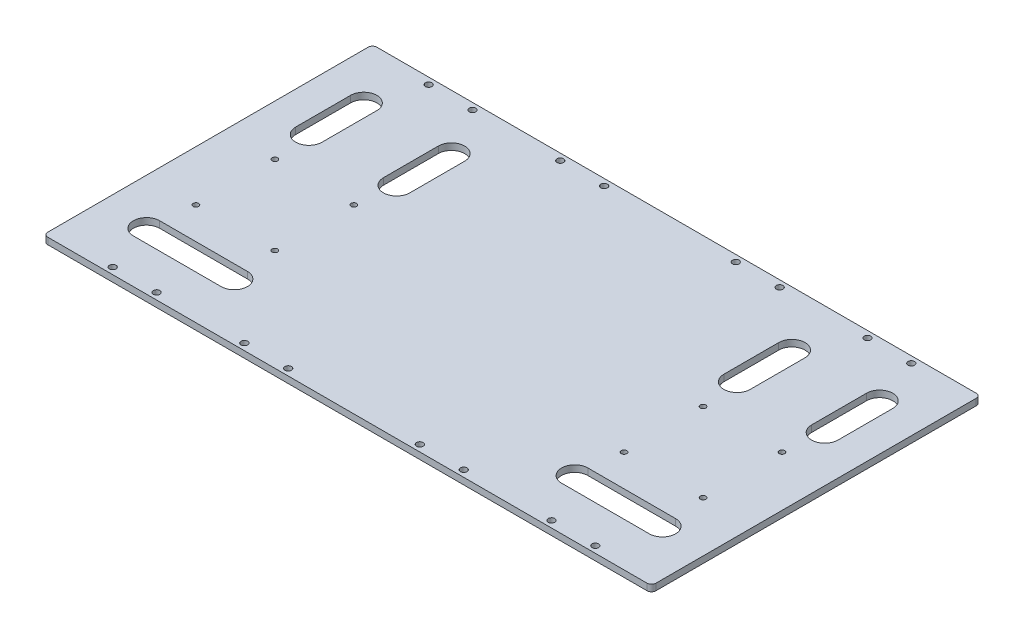
SolidWorks part; units mm, degrees
ref_plane "前视基准面" through (0, 0, 0) normal (0, 0, 1) x (1, 0, 0)
ref_plane "上视基准面" through (0, 0, 0) normal (0, 1, 0) x (1, 0, 0)
ref_plane "右视基准面" through (0, 0, 0) normal (1, 0, 0) x (0, 0, -1)
other "Configuration Table"
sketch "草图1" plane through (0, 0, 0) normal (0, 1, 0) x (1, 0, 0)
  line L9 (-138.5819, 57.4025) -> (-57.4025, 138.5819) construction
  line L10 (-138.5819, 57.4025) -> (138.5819, 57.4025)
  line L11 (-138.5819, 57.4025) -> (-138.5819, -57.4025) construction
  line L12 (-138.5819, -57.4025) -> (138.5819, -57.4025) construction
  line L13 (138.5819, 57.4025) -> (138.5819, -57.4025) construction
  line L14 (-138.5819, 57.4025) -> (138.5819, -57.4025) construction
  line L15 (-138.5819, -57.4025) -> (138.5819, 57.4025) construction
  line L16 (-57.4025, 138.5819) -> (57.4025, 138.5819) construction
  line L17 (57.4025, 138.5819) -> (138.5819, 57.4025) construction
  line L18 (-138.5819, -57.4025) -> (-57.4025, -138.5819) construction
  line L19 (-57.4025, -138.5819) -> (57.4025, -138.5819) construction
  line L20 (57.4025, -138.5819) -> (138.5819, -57.4025) construction
  line L21 (-138.5819, 57.4025) -> (-138.5819, 207.4025)
  line L22 (-138.5819, 207.4025) -> (138.5819, 207.4025)
  line L23 (138.5819, 207.4025) -> (138.5819, 57.4025)
  point P0 (0, 0)
  dimension "D1" = 135
  dimension "D2" = 300
  dimension "D3" = 150
extrude "凸台-拉伸1" add sketch "草图1" along normal blind 3
sketch "草图2" plane through (0, 3, 0) normal (0, 1, 0) x (1, 0, 0)
  line L0 (0, 57.4025) -> (0, 207.4025) construction
  line L1 (-138.5819, 57.4025) -> (138.5819, 57.4025) construction
  line L2 (138.5819, 207.4025) -> (-138.5819, 207.4025) construction
  line L3 (-50, 60.4025) -> (-30, 60.4025) construction
  line L4 (-110, 60.4025) -> (-90, 60.4025) construction
  line L5 (0, 132.4025) -> (138.5819, 132.4025) construction
  line L6 (110, 60.4025) -> (90, 60.4025) construction
  line L7 (50, 60.4025) -> (30, 60.4025) construction
  line L8 (138.5819, 57.4025) -> (138.5819, 207.4025) construction
  line L9 (50, 204.4025) -> (30, 204.4025) construction
  line L10 (110, 204.4025) -> (90, 204.4025) construction
  line L11 (-110, 204.4025) -> (-90, 204.4025) construction
  line L12 (-50, 204.4025) -> (-30, 204.4025) construction
  circle A0 centre (-50, 60.4025) radius 1.5
  circle A1 centre (-30, 60.4025) radius 1.5
  circle A2 centre (-110, 60.4025) radius 1.5
  circle A3 centre (-90, 60.4025) radius 1.5
  circle A4 centre (90, 60.4025) radius 1.5
  circle A5 centre (110, 60.4025) radius 1.5
  circle A6 centre (30, 60.4025) radius 1.5
  circle A7 centre (50, 60.4025) radius 1.5
  circle A8 centre (50, 204.4025) radius 1.5
  circle A9 centre (30, 204.4025) radius 1.5
  circle A10 centre (110, 204.4025) radius 1.5
  circle A11 centre (90, 204.4025) radius 1.5
  circle A12 centre (-90, 204.4025) radius 1.5
  circle A13 centre (-110, 204.4025) radius 1.5
  circle A14 centre (-30, 204.4025) radius 1.5
  circle A15 centre (-50, 204.4025) radius 1.5
  dimension "D3" = 3
  dimension "D1" = 20
  dimension "D2" = 20
  dimension "D4" = 3
  dimension "D5" = 30
  dimension "D6" = 40
extrude "切除-拉伸1" cut sketch "草图2" against normal blind 10
sketch "草图3" plane through (0, 3, 0) normal (0, 1, 0) x (1, 0, 0)
  line L0 (-117.5819, 83.4025) -> (-77.5819, 83.4025) construction
  line L1 (-117.5819, 89.4025) -> (-77.5819, 89.4025)
  line L2 (-117.5819, 77.4025) -> (-77.5819, 77.4025)
  line L3 (0, 0) -> (0, 57.4025) construction
  line L4 (-138.5819, 57.4025) -> (138.5819, 57.4025) construction
  line L5 (-117.5819, 182.4025) -> (-117.5819, 157.4025) construction
  line L6 (-111.5819, 182.4025) -> (-111.5819, 157.4025)
  line L7 (-123.5819, 182.4025) -> (-123.5819, 157.4025)
  line L8 (-77.5819, 182.4025) -> (-77.5819, 157.4025) construction
  line L9 (-71.5819, 182.4025) -> (-71.5819, 157.4025)
  line L10 (-83.5819, 182.4025) -> (-83.5819, 157.4025)
  line L11 (-117.5819, 157.4025) -> (-117.5819, 83.4025) construction
  line L14 (117.5819, 83.4025) -> (77.5819, 83.4025) construction
  line L15 (117.5819, 89.4025) -> (77.5819, 89.4025)
  line L16 (117.5819, 77.4025) -> (77.5819, 77.4025)
  line L17 (-77.5819, 157.4025) -> (-77.5819, 83.4025) construction
  line L18 (138.5819, 207.4025) -> (-138.5819, 207.4025) construction
  line L19 (-138.5819, 207.4025) -> (-138.5819, 57.4025) construction
  line L26 (117.5819, 182.4025) -> (117.5819, 157.4025) construction
  line L27 (111.5819, 182.4025) -> (111.5819, 157.4025)
  line L28 (123.5819, 182.4025) -> (123.5819, 157.4025)
  line L29 (77.5819, 182.4025) -> (77.5819, 157.4025) construction
  line L30 (71.5819, 182.4025) -> (71.5819, 157.4025)
  line L31 (83.5819, 182.4025) -> (83.5819, 157.4025)
  line L32 (77.5819, 157.4025) -> (77.5819, 83.4025) construction
  line L33 (117.5819, 157.4025) -> (117.5819, 83.4025) construction
  line L46 (-37.5819, 182.4025) -> (-37.5819, 157.4025) construction
  line L47 (-31.5819, 182.4025) -> (-31.5819, 157.4025)
  line L48 (-43.5819, 182.4025) -> (-43.5819, 157.4025)
  line L49 (-37.5819, 182.4025) -> (-37.5819, 157.4025) construction
  line L50 (-31.5819, 182.4025) -> (-31.5819, 157.4025)
  line L51 (-43.5819, 182.4025) -> (-43.5819, 157.4025)
  arc A0 (-117.5819, 89.4025) -> (-117.5819, 77.4025) centre (-117.5819, 83.4025) ccw
  arc A1 (-77.5819, 77.4025) -> (-77.5819, 89.4025) centre (-77.5819, 83.4025) ccw
  arc A2 (-111.5819, 182.4025) -> (-123.5819, 182.4025) centre (-117.5819, 182.4025) ccw
  arc A3 (-123.5819, 157.4025) -> (-111.5819, 157.4025) centre (-117.5819, 157.4025) ccw
  arc A4 (-71.5819, 182.4025) -> (-83.5819, 182.4025) centre (-77.5819, 182.4025) ccw
  arc A5 (-83.5819, 157.4025) -> (-71.5819, 157.4025) centre (-77.5819, 157.4025) ccw
  arc A8 (117.5819, 89.4025) -> (117.5819, 77.4025) centre (117.5819, 83.4025) cw
  arc A9 (77.5819, 77.4025) -> (77.5819, 89.4025) centre (77.5819, 83.4025) cw
  arc A10 (111.5819, 182.4025) -> (123.5819, 182.4025) centre (117.5819, 182.4025) cw
  arc A11 (123.5819, 157.4025) -> (111.5819, 157.4025) centre (117.5819, 157.4025) cw
  arc A14 (71.5819, 182.4025) -> (83.5819, 182.4025) centre (77.5819, 182.4025) cw
  arc A15 (83.5819, 157.4025) -> (71.5819, 157.4025) centre (77.5819, 157.4025) cw
  arc A26 (-31.5819, 182.4025) -> (-43.5819, 182.4025) centre (-37.5819, 182.4025) ccw
  arc A27 (-43.5819, 157.4025) -> (-31.5819, 157.4025) centre (-37.5819, 157.4025) ccw
  point P2 (-97.5819, 83.4025)
  point P14 (-117.5819, 169.9025)
  point P22 (-77.5819, 169.9025)
  point P35 (-33.5819, 169.9025)
  point P36 (97.5819, 83.4025)
  point P45 (-33.5819, 169.9025)
  point P52 (-33.5819, 169.9025)
  point P60 (117.5819, 169.9025)
  point P67 (77.5819, 169.9025)
  point P78 (-33.5819, 169.9025)
  point P85 (-33.5819, 169.9025)
  point P92 (-33.5819, 169.9025)
  point P99 (-37.5819, 169.9025)
  point P106 (-37.5819, 169.9025)
  point P113 (-37.5819, 169.9025)
  dimension "D1" = 6
  dimension "D3" = 6
  dimension "D2" = 20
  dimension "D5" = 25
  dimension "D6" = 25
  dimension "D7" = 40
  dimension "D8" = 15
  dimension "D4" = 3
extrude "切除-拉伸2" cut sketch "草图3" against normal blind 10
fillet "圆角1" radius 2 4 edges at (-138.5819, 1.5, -207.4025) (138.5819, 1.5, -207.4025) (138.5819, 1.5, -57.4025) (-138.5819, 1.5, -57.4025)
sketch "草图4" plane through (0, 3, 0) normal (0, 1, 0) x (1, 0, 0)
  line L0 (-111.5819, 169.9025) -> (-83.5819, 169.9025) construction
  line L1 (-115.5819, 139.9025) -> (-79.5819, 139.9025) construction
  line L2 (-115.5819, 139.9025) -> (-115.5819, 103.9025) construction
  line L3 (-115.5819, 103.9025) -> (-79.5819, 103.9025) construction
  line L4 (-79.5819, 139.9025) -> (-79.5819, 103.9025) construction
  line L5 (-115.5819, 139.9025) -> (-79.5819, 103.9025) construction
  line L6 (-115.5819, 103.9025) -> (-79.5819, 139.9025) construction
  line L7 (-111.5819, 157.4025) -> (-111.5819, 182.4025) construction
  line L8 (-83.5819, 182.4025) -> (-83.5819, 157.4025) construction
  line L9 (-97.5819, 169.9025) -> (-97.5819, 139.9025) construction
  line L10 (0, 57.4025) -> (0, 207.4025) construction
  line L11 (-136.5819, 57.4025) -> (136.5819, 57.4025) construction
  line L12 (136.5819, 207.4025) -> (-136.5819, 207.4025) construction
  line L13 (97.5819, 169.9025) -> (97.5819, 139.9025) construction
  line L14 (115.5819, 103.9025) -> (79.5819, 139.9025) construction
  line L15 (115.5819, 139.9025) -> (79.5819, 103.9025) construction
  line L16 (79.5819, 139.9025) -> (79.5819, 103.9025) construction
  line L17 (115.5819, 103.9025) -> (79.5819, 103.9025) construction
  line L18 (115.5819, 139.9025) -> (115.5819, 103.9025) construction
  line L19 (115.5819, 139.9025) -> (79.5819, 139.9025) construction
  line L20 (111.5819, 169.9025) -> (83.5819, 169.9025) construction
  circle A0 centre (-115.5819, 139.9025) radius 1.25
  circle A1 centre (-79.5819, 139.9025) radius 1.25
  circle A2 centre (-79.5819, 103.9025) radius 1.25
  circle A3 centre (-115.5819, 103.9025) radius 1.25
  circle A6 centre (115.5819, 103.9025) radius 1.25
  circle A7 centre (79.5819, 103.9025) radius 1.25
  circle A8 centre (79.5819, 139.9025) radius 1.25
  circle A9 centre (115.5819, 139.9025) radius 1.25
  point P0 (-97.5819, 121.9025)
  point P23 (0, 57.4025)
  point P36 (97.5819, 121.9025)
  dimension "D2" = 2.5
  dimension "D1" = 36
  dimension "D3" = 30
extrude "中心板安装孔" cut sketch "草图4" against normal blind 10
